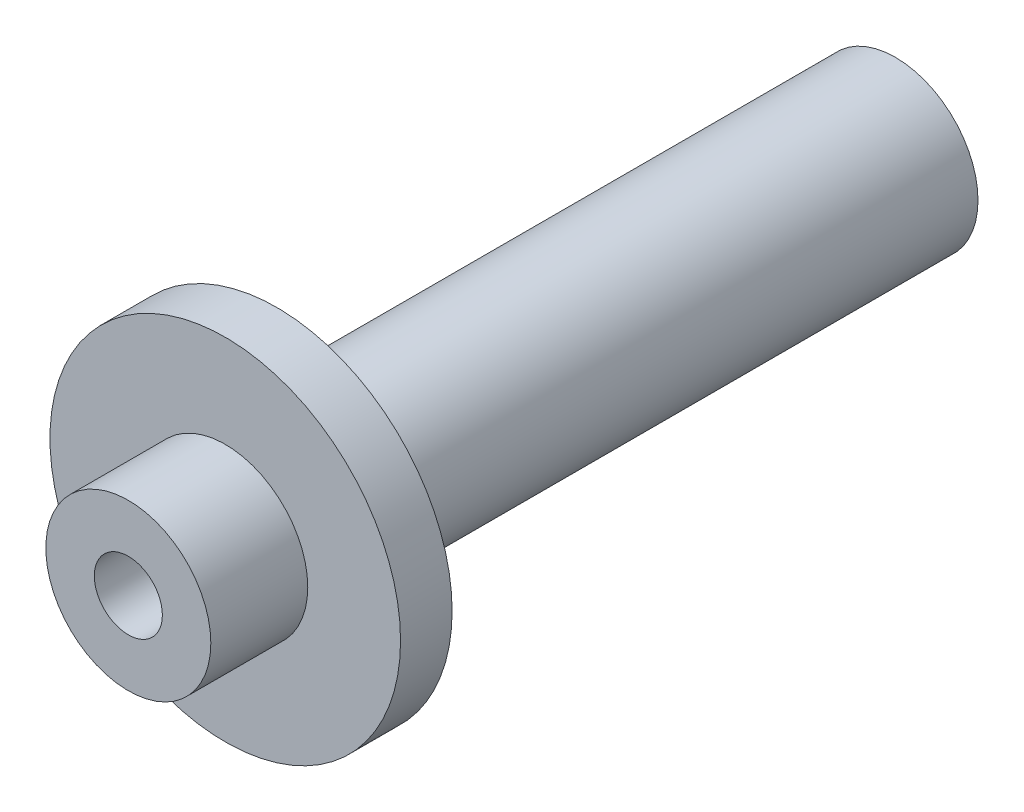
SolidWorks part; units mm, degrees
ref_plane "Спереди" through (0, 0, 0) normal (0, 0, 1) x (1, 0, 0)
ref_plane "Сверху" through (0, 0, 0) normal (0, 1, 0) x (1, 0, 0)
ref_plane "Справа" through (0, 0, 0) normal (1, 0, 0) x (0, 0, -1)
sketch "Эскиз1" plane through (0, 0, 0) normal (0, 0, 1) x (1, 0, 0)
  circle A0 centre (0, 0) radius 8.5
  dimension "D1" = 17
extrude "Бобышка-Вытянуть1" add sketch "Эскиз1" along normal blind 2.5
sketch "Эскиз2" plane through (0, 0, 2.5) normal (0, 0, 1) x (1, 0, 0)
  circle A0 centre (0, 0) radius 4
  dimension "D1" = 8
extrude "Бобышка-Вытянуть2" add sketch "Эскиз2" along normal blind 4.7
sketch "Эскиз3" plane through (0, 0, 7.2) normal (0, 0, 1) x (1, 0, 0)
  circle A0 centre (0, 0) radius 1.65
  dimension "D1" = 3.3
extrude "Вырез-Вытянуть1" cut sketch "Эскиз3" against normal blind 12
sketch "Эскиз4" plane through (0, 0, 0) normal (0, 0, -1) x (-1, 0, 0)
  circle A0 centre (0, 0) radius 4
  dimension "D1" = 8
extrude "Бобышка-Вытянуть3" add sketch "Эскиз4" along normal blind 30
